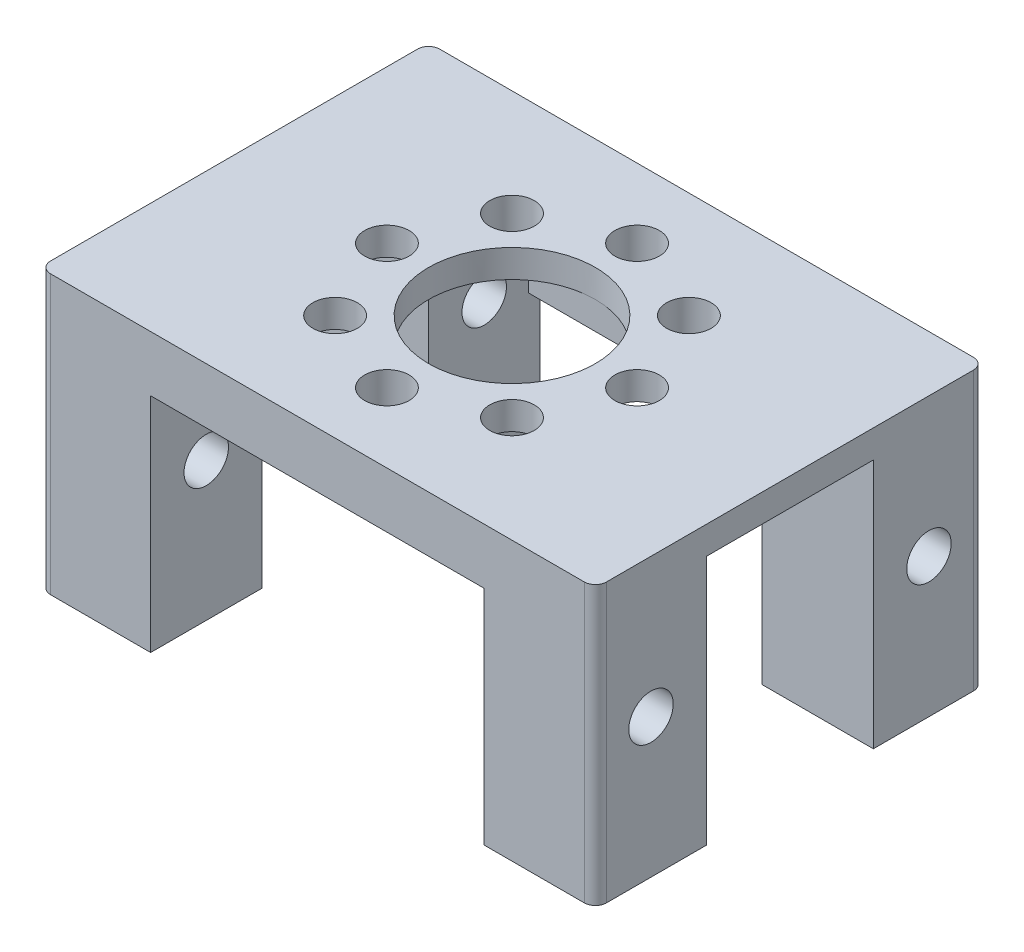
SolidWorks part; units mm, degrees
ref_plane "Plano frontal" through (0, 0, 0) normal (0, 0, 1) x (1, 0, 0)
ref_plane "Plano superior" through (0, 0, 0) normal (0, 1, 0) x (1, 0, 0)
ref_plane "Plano direito" through (0, 0, 0) normal (1, 0, 0) x (0, 0, -1)
sketch "Esboço1" plane through (0, 0, 0) normal (0, 1, 0) x (1, 0, 0)
  line L1 (0, 0) -> (100, 0)
  line L2 (0, 0) -> (0, 70)
  line L3 (0, 70) -> (100, 70)
  line L4 (100, 0) -> (100, 70)
  dimension "D1" = 100
  dimension "D2" = 70
extrude "Ressalto-extrusão1" add sketch "Esboço1" against normal blind 50
sketch "Esboço2" plane through (0, 0, 0) normal (1, 0, 0) x (0, 0, -1)
  line L0 (0, -50) -> (70, -50) construction
  line L1 (50, -95) -> (20, -95)
  line L2 (50, -95) -> (50, -5)
  line L3 (50, -5) -> (20, -5)
  line L4 (20, -95) -> (20, -5)
  line L5 (50, -95) -> (20, -5) construction
  line L6 (50, -5) -> (20, -95) construction
  line L7 (0, 0) -> (70, 0) construction
  line L8 (70, -50) -> (70, 0) construction
  line L9 (0, 27.5) -> (0, -27.5) construction
  point P0 (35, -50)
  dimension "D1" = 5
  dimension "D2" = 20
  dimension "D3" = 20
extrude "Corte-extrusão1" cut sketch "Esboço2" along normal blind 239 contours L2 L1 L4 L3
sketch "Esboço3" plane through (100, 0, 0) normal (1, 0, 0) x (0, 0, -1)
  line L1 (0, 0) -> (70, 0) construction
  circle A0 centre (10, -25) radius 4
  circle A2 centre (10, -25) radius 4
  circle A3 centre (60, -25) radius 4
  dimension "D2" = 8
  dimension "D3" = 8
  dimension "D1" = 25
extrude "Corte-extrusão2" cut sketch "Esboço3" against normal up to surface (100 mm away) from surface at 0 contours A0 | A3 up to face at (0, -26.25, -35) starting at face at (100, -26.25, -35)
sketch "Esboço4" plane through (0, 0, 0) normal (0, 0, 1) x (1, 0, 0)
  line L0 (0, -50) -> (100, -50) construction
  line L1 (80, -90) -> (20, -90)
  line L2 (80, -90) -> (80, -10)
  line L3 (80, -10) -> (20, -10)
  line L4 (20, -90) -> (20, -10)
  line L5 (80, -90) -> (20, -10) construction
  line L6 (80, -10) -> (20, -90) construction
  line L7 (0, 0) -> (100, 0) construction
  line L8 (0, -50) -> (0, 0) construction
  point P0 (50, -50)
  dimension "D1" = 10
  dimension "D2" = 20
extrude "Corte-extrusão3" cut sketch "Esboço4" against normal up to surface (70 mm away) contours L2 L1 L4 L3 up to face at (50, -25, -70)
fillet "Filete2" radius 2 1 edges at (0, -25, -70)
fillet "Filete3" radius 2 3 edges at (100, -25, -70) (100, -25, 0) (0, -25, 0)
sketch "Esboço5" plane through (0, 0, 0) normal (0, 1, 0) x (1, 0, 0)
  circle A0 centre (50, 35) radius 15
  dimension "D1" = 30
extrude "Corte-extrusão4" cut sketch "Esboço5" against normal up to surface (5 mm away) up to face at (50, -5, -35)
sketch "Esboço6" plane through (0, 0, 0) normal (0, 1, 0) x (1, 0, 0)
  line L0 (98, 70) -> (2, 70) construction
  circle A0 centre (50, 57.5) radius 4
  dimension "D1" = 12.5
  dimension "D2" = 8
extrude "Corte-extrusão7" cut sketch "Esboço6" against normal blind 239
pattern_circular "PadrãoCircular1" count 8 every 45 about axis through (50, 0, -35) along (0, 1, 0) of "Corte-extrusão7"
